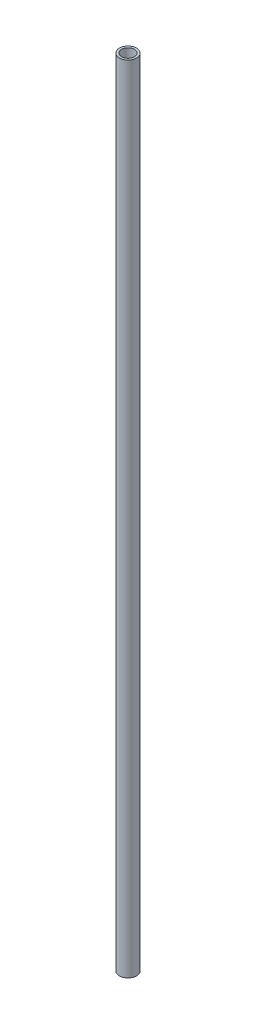
SolidWorks part; units mm, degrees
material "windcatcher"
ref_plane "Front Plane" through (0, 0, 0) normal (0, 0, 1) x (1, 0, 0)
ref_plane "Top Plane" through (0, 0, 0) normal (0, 1, 0) x (1, 0, 0)
ref_plane "Right Plane" through (0, 0, 0) normal (1, 0, 0) x (0, 0, -1)
sketch "Sketch1" plane through (0, 0, 0) normal (0, 1, 0) x (1, 0, 0)
  circle A0 centre (0, 0) radius 3
  circle A1 centre (0, 0) radius 4
  dimension "D1" = 6
  dimension "D2" = 8
extrude "Boss-Extrude1" add sketch "Sketch1" along normal blind 370
